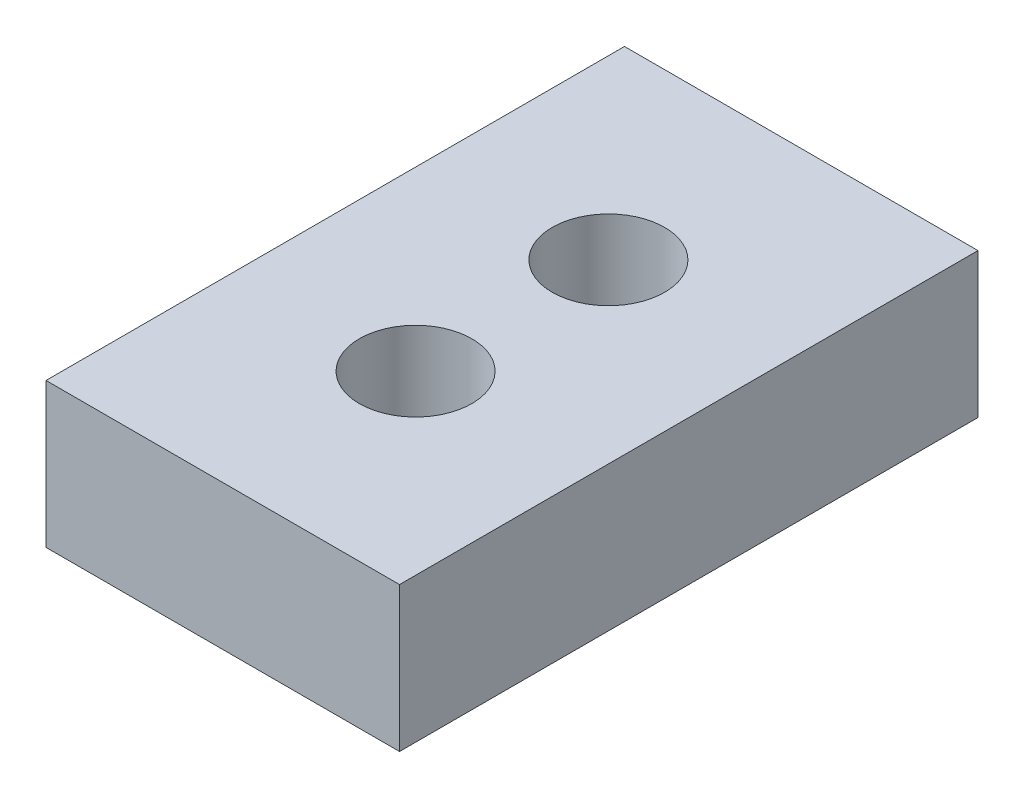
SolidWorks part; units mm, degrees
ref_plane "Front Plane" through (0, 0, 0) normal (0, 0, 1) x (1, 0, 0)
ref_plane "Top Plane" through (0, 0, 0) normal (0, 1, 0) x (1, 0, 0)
ref_plane "Right Plane" through (0, 0, 0) normal (1, 0, 0) x (0, 0, -1)
sketch "Sketch1" plane through (0, 0, 0) normal (0, 1, 0) x (1, 0, 0)
  line L0 (-5.5, 9) -> (-5.5, -9)
  line L1 (-5.5, 9) -> (5.5, 9)
  line L2 (-5.5, -9) -> (5.5, -9)
  line L3 (5.5, 9) -> (5.5, -9)
  line L4 (-5.5, 9) -> (5.5, -9) construction
  line L5 (-5.5, -9) -> (5.5, 9) construction
  point P1 (0, 0)
  dimension "D1" = 11
  dimension "D2" = 18
extrude "Boss-Extrude1" add sketch "Sketch1" along normal blind 4.5
sketch "Sketch2" plane through (0, 4.5, 0) normal (0, 1, 0) x (1, 0, 0)
  circle A0 centre (0, -3) radius 1.75
  circle A1 centre (0, 3) radius 1.75
  dimension "D3" = 3.5
  dimension "D4" = 3.5
  dimension "D1" = 3
  dimension "D2" = 3
extrude "Cut-Extrude1" cut sketch "Sketch2" against normal blind 4.5
